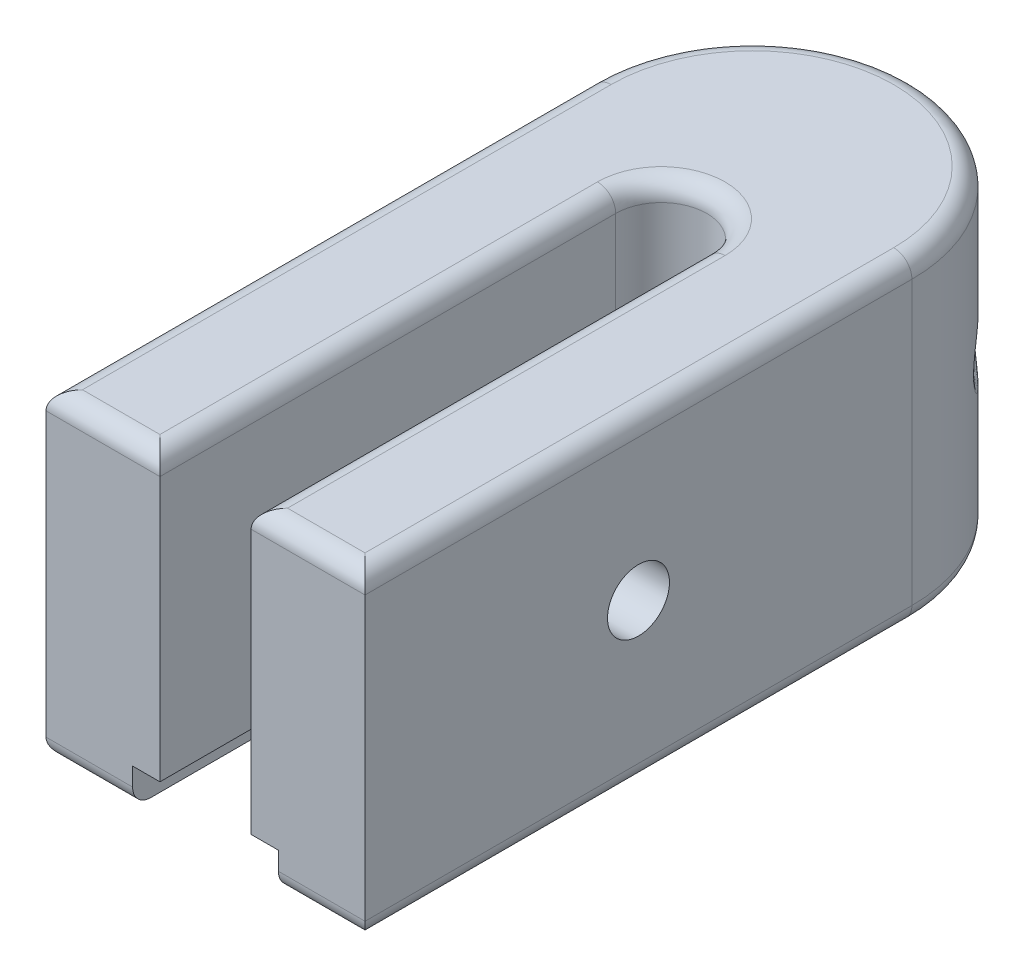
SolidWorks part; units mm, degrees
material "PET"
ref_plane "Front Plane" through (0, 0, 0) normal (0, 0, 1) x (1, 0, 0)
ref_plane "Top Plane" through (0, 0, 0) normal (0, 1, 0) x (1, 0, 0)
ref_plane "Right Plane" through (0, 0, 0) normal (1, 0, 0) x (0, 0, -1)
sketch "Sketch1" plane through (0, 0, 0) normal (0, 0, 1) x (1, 0, 0)
  line L1 (-12.7, 12.7) -> (12.7, 12.7) construction
  line L2 (-12.7, 12.7) -> (-12.7, -12.7) construction
  line L3 (-12.7, -12.7) -> (12.7, -12.7) construction
  line L4 (12.7, 12.7) -> (12.7, -12.7) construction
  line L5 (-12.7, 12.7) -> (12.7, -12.7) construction
  line L6 (-12.7, -12.7) -> (12.7, 12.7) construction
  line L7 (-11.1125, 11.1125) -> (11.1125, 11.1125)
  line L8 (-11.1125, 11.1125) -> (-11.1125, -11.1125)
  line L9 (-11.1125, -11.1125) -> (11.1125, -11.1125)
  line L10 (11.1125, 11.1125) -> (11.1125, -11.1125)
  line L11 (-11.1125, 11.1125) -> (11.1125, -11.1125) construction
  line L12 (-11.1125, -11.1125) -> (11.1125, 11.1125) construction
  point P0 (0, 0)
  point P6 (0, 0)
  dimension "D1" = 25.4
  dimension "D2" = 25.4
  dimension "D3" = 1.5875
extrude "Boss-Extrude1" add sketch "Sketch1" along normal blind 38.1
ref_plane "Plane1" through (0, 0, 0) normal (0, 1, 0) x (1, 0, 0)
sketch "Sketch3" plane through (0, 0, 0) normal (0, 1, 0) x (1, 0, 0)
  line L0 (11.1125, 0) -> (-11.1125, 0) construction
  line L1 (-11.1125, 0) -> (11.1125, 0)
  arc A0 (-11.1125, 0) -> (11.1125, 0) centre (0, 0) cw
extrude "Boss-Extrude3" add sketch "Sketch3" along normal up to surface and the other way up to surface up to face at (0, 11.1125, 19.05) other way up to face at (0, -11.1125, 19.05)
sketch "Sketch4" plane through (11.1125, 0, 0) normal (1, 0, 0) x (0, 0, -1)
  line L0 (-38.1, 0) -> (0, 0) construction
  line L1 (-38.1, -11.1125) -> (-38.1, 11.1125) construction
  line L2 (-19.05, 11.1125) -> (-19.05, -11.1125) construction
  line L3 (-38.1, 11.1125) -> (0, 11.1125) construction
  line L4 (-38.1, -11.1125) -> (0, -11.1125) construction
  line L5 (-38.1, 0) -> (0, 0) construction
  circle A0 centre (-19.05, 0) radius 2.159
  dimension "D1" = 4.318
extrude "Cut-Extrude1" cut sketch "Sketch4" against normal through all
sketch "Sketch5" plane through (0, 0, 0) normal (0, 1, 0) x (1, 0, 0)
  line L0 (0, 0) -> (-7.8577, 7.8577)
  line L1 (0, 0) -> (7.8577, 7.8577)
  line L3 (0, 24.9211) -> (0, -38.8695) construction
  arc A0 (11.1125, 0) -> (-11.1125, 0) centre (0, 0) ccw construction
  dimension "D1" = 45
  dimension "D2" = 45
ref_plane "Plane2" through (-7.8577, 0, -7.8577) normal (0.7071, 0, 0.7071) x (0.7071, 0, -0.7071)
sketch "Sketch7" plane through (-7.8577, 0, -7.8577) normal (0.7071, 0, 0.7071) x (0.7071, 0, -0.7071)
  circle A0 centre (0, 0) radius 1.5875
  dimension "D1" = 3.175
ref_plane "Plane3" through (7.8577, 0, -7.8577) normal (0.7071, 0, -0.7071) x (-0.7071, 0, -0.7071)
sketch "Sketch8" plane through (7.8577, 0, -7.8577) normal (0.7071, 0, -0.7071) x (-0.7071, 0, -0.7071)
  circle A0 centre (0, 0) radius 1.5875
  dimension "D1" = 3.175
extrude "Cut-Extrude3" cut sketch "Sketch8" against normal blind 8.89 contours A0
extrude "Cut-Extrude4" cut sketch "Sketch7" along normal blind 8.89 contours A0
sketch "Sketch10" plane through (0, -11.1125, 0) normal (0, -1, 0) x (-1, 0, 0)
  line L0 (0, -38.1) -> (0, 0) construction
  line L1 (11.1125, -38.1) -> (-11.1125, -38.1) construction
  line L2 (0, -6.35) -> (0, -44.45) construction
  line L3 (3.175, -6.35) -> (3.175, -44.45)
  line L4 (-3.175, -6.35) -> (-3.175, -44.45)
  arc A0 (3.175, -6.35) -> (-3.175, -6.35) centre (0, -6.35) ccw
  arc A1 (-3.175, -44.45) -> (3.175, -44.45) centre (0, -44.45) ccw
  point P7 (0, -25.4)
  dimension "D1" = 38.1
  dimension "D2" = 6.35
  dimension "D3" = 6.35
extrude "Cut-Extrude6" cut sketch "Sketch10" against normal through all
fillet "Fillet1" radius 0.508 2 edges at (8.8764, 0.347, -6.6856) (-6.6856, -0.347, -8.8764)
fillet "Fillet14" [suppressed] radius 0.508
sketch "Sketch14" plane through (0, 0, 0) normal (0, 1, 0) x (1, 0, 0)
  line L0 (0.3326, 2.2253) -> (-2.1037, -0.2111)
  line L1 (-2.1037, -0.2111) -> (0.0829, -2.3977)
  line L2 (0.0829, -2.3977) -> (2.5192, 0.0387)
  line L3 (2.5192, 0.0387) -> (0.3326, 2.2253)
  line L4 (0, 0) -> (-7.8577, 7.8577) construction
sketch "Sketch15" plane through (0, -11.1125, 0) normal (0, -1, 0) x (1, 0, 0)
  line L0 (-7.9375, 0) -> (7.9375, 0)
  line L4 (11.1125, 38.1) -> (3.175, 38.1)
  line L8 (11.1125, 38.1) -> (3.175, 38.1)
  line L9 (-3.175, 38.1) -> (-11.1125, 38.1)
  line L10 (-3.175, 38.1) -> (-11.1125, 38.1)
  line L11 (-3.175, 6.35) -> (-3.175, 38.1)
  line L12 (-3.175, 6.35) -> (-3.175, 38.1)
  line L13 (3.175, 38.1) -> (3.175, 6.35)
  line L14 (3.175, 38.1) -> (3.175, 6.35)
  line L18 (-11.1125, 38.1) -> (-11.1125, 0)
  line L19 (-11.1125, 38.1) -> (-11.1125, 0)
  line L20 (11.1125, 0) -> (11.1125, 38.1)
  line L21 (11.1125, 0) -> (11.1125, 38.1)
  arc A1 (-11.1125, 0) -> (11.1125, 0) centre (0, 0) ccw
  arc A2 (-11.1125, 0) -> (11.1125, 0) centre (0, 0) ccw
  arc A4 (-3.175, 6.35) -> (3.175, 6.35) centre (0, 6.35) ccw
  arc A5 (-3.175, 6.35) -> (3.175, 6.35) centre (0, 6.35) ccw
  dimension "D1" = 0
fillet "Fillet15" radius 1.27 16 edges at (-7.1438, -11.1125, 38.1) (7.1437, -11.1125, 38.1) (11.1125, -11.1125, 19.05) (0, 11.1125, -11.1125) (0, -11.1125, -11.1125) (-11.1125, -11.1125, 19.05) (-7.1438, 11.1125, 38.1) (7.1437, 11.1125, 38.1) (-11.1125, 11.1125, 19.05) (11.1125, 11.1125, 19.05) (3.175, -11.1125, 22.225) (-3.175, -11.1125, 22.225) (0, -11.1125, 3.175) (3.175, 11.1125, 22.225) (0, 11.1125, 3.175) (-3.175, 11.1125, 22.225)
sketch "Sketch17" plane through (0, 0, 38.1) normal (0, 0, 1) x (1, 0, 0)
extrude "Boss-Extrude15" add sketch "Sketch14" along normal mid plane 5.08
sketch "Sketch18" plane through (0, 0, 38.1) normal (0, 0, 1) x (1, 0, 0)
  line L1 (5.08, -8.5725) -> (-5.08, -8.5725)
  line L2 (5.08, -8.5725) -> (5.08, -14.6926)
  line L3 (5.08, -14.6926) -> (-5.08, -14.6926)
  line L4 (-5.08, -8.5725) -> (-5.08, -14.6926)
  line L5 (-3.175, -11.1125) -> (-11.1125, -11.1125) construction
  point P4 (0, -8.5725)
  dimension "D1" = 2.54
  dimension "D2" = 10.16
extrude "Cut-Extrude7" cut sketch "Sketch18" against normal blind 36.83
equation "\"0..015in\"=0.625"
